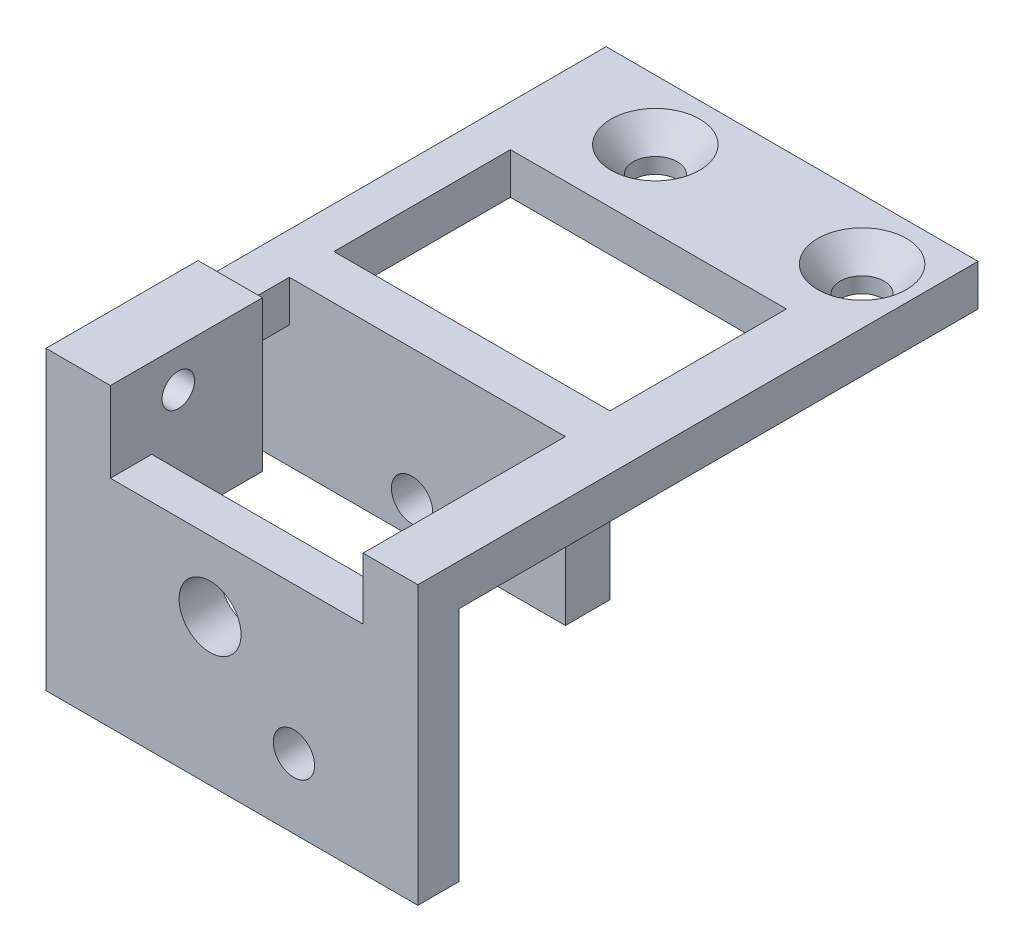
SolidWorks part; units mm, degrees
material "ABS"
ref_plane "Front Plane" through (0, 0, 0) normal (0, 0, 1) x (1, 0, 0)
ref_plane "Top Plane" through (0, 0, 0) normal (0, 1, 0) x (1, 0, 0)
ref_plane "Right Plane" through (0, 0, 0) normal (1, 0, 0) x (0, 0, -1)
sketch "Sketch1" plane through (0, 0, 0) normal (0, 0, 1) x (1, 0, 0)
  line L0 (0, 8.8442) -> (12.8921, -2.9343) construction
  line L1 (23.5226, 29.0697) -> (31.9421, 29.0697)
  line L2 (-25.2079, 8.8442) -> (-25.2079, -13.6023)
  line L3 (-25.2079, -13.6023) -> (31.9421, -13.6023)
  line L4 (31.9421, 29.0697) -> (31.9421, -13.6023)
  line L6 (-25.2079, 8.8442) -> (-25.2079, 31.9582)
  line L7 (-25.2079, 31.9582) -> (-18.8579, 31.9582)
  line L11 (23.5226, 22.6565) -> (23.5226, 29.0697)
  line L12 (-18.8579, 31.9582) -> (-15.3109, 31.9582)
  line L14 (-15.3109, 31.9582) -> (-15.3109, 22.6565)
  line L15 (-15.3109, 22.6565) -> (-15.3109, 19.6203)
  line L16 (-15.3109, 19.6203) -> (23.5226, 19.6203)
  line L17 (23.5226, 19.6203) -> (23.5226, 22.6565)
  circle A0 centre (12.8921, -2.9343) radius 3.175
  circle A1 centre (0, 8.8442) radius 4.7625
  dimension "D5" = 9.525
  dimension "D9" = 6.35
  dimension "D1" = 23.114
  dimension "D2" = 57.15
  dimension "D3" = 42.672
  dimension "D4" = 6.35
  dimension "D6" = 19.05
  dimension "D7" = 10.668
  dimension "D8" = 17.4625
extrude "Boss-Extrude1" add sketch "Sketch1" against normal blind 6.35
sketch "Sketch2" plane through (0, 0, 0) normal (0, 0, 1) x (1, 0, 0)
  line L0 (-25.2079, 31.9582) -> (-25.2079, -13.6023) construction
  line L1 (-18.8579, 31.9582) -> (-25.2079, 31.9582)
  line L3 (-18.8579, 8.8442) -> (-25.2079, 8.8442)
  line L4 (-25.2079, 31.9582) -> (-25.2079, 8.8442)
  line L6 (-15.3109, 31.9582) -> (-25.2079, 31.9582)
  line L7 (-15.3109, 31.9582) -> (-15.3109, 8.8442)
  line L8 (-15.3109, 8.8442) -> (-25.2079, 8.8442)
  line L9 (-25.2079, 31.9582) -> (-25.2079, 8.8442)
  line M4 (-15.3109, 31.9582) -> (-25.2079, 31.9582)
  line M5 (-25.2079, 31.9582) -> (-25.2079, -13.6023)
  line M15 (-15.3109, 19.6203) -> (-15.3109, 31.9582)
  dimension "D1" = 23.114
extrude "Boss-Extrude2" add sketch "Sketch2" against normal blind 23.368 contours L8 L7 L3 M15 M4 M5
sketch "Sketch3" plane through (0, 29.0697, 0) normal (0, 1, 0) x (1, 0, 0)
  line L0 (-25.2079, 23.368) -> (-25.2079, 0) construction
  line L1 (-18.8579, 0) -> (-25.2079, 0)
  line L2 (-18.8579, 0) -> (-18.8579, 78.34)
  line L3 (-18.8579, 78.34) -> (-25.2079, 78.34)
  line L4 (-25.2079, 0) -> (-25.2079, 78.34)
  line L5 (31.9421, 0) -> (23.5601, 0)
  line L6 (31.9421, 0) -> (31.9421, 78.34)
  line L7 (31.9421, 78.34) -> (23.5601, 78.34)
  line L8 (23.5601, 0) -> (23.5601, 78.34)
  dimension "D2" = 8.382
  dimension "D3" = 78.34
  dimension "D4" = 78.34
extrude "Boss-Extrude3" add sketch "Sketch3" against normal blind 6.35
sketch "Sketch4" plane through (-25.2079, 0, 0) normal (-1, 0, 0) x (0, 0, 1)
  circle A0 centre (-10.4375, 26.1623) radius 2.5
  dimension "D1" = 5
extrude "Cut-Extrude1" cut sketch "Sketch4" against normal up to next
sketch "Sketch5" plane through (0, 29.0697, 0) normal (0, 1, 0) x (1, 0, 0)
  line L0 (31.9421, 78.34) -> (31.9421, 0) construction
  line L2 (-25.2079, 78.34) -> (-25.2079, 65.0226)
  line L3 (-25.2079, 65.0226) -> (31.9421, 65.0226)
  line L4 (31.9421, 78.34) -> (31.9421, 65.0226)
  line L5 (-25.2079, 78.34) -> (-25.2079, 23.368) construction
  line L9 (-25.2079, 78.34) -> (-25.2079, 86.0813)
  line L10 (-25.2079, 86.0813) -> (31.9421, 86.0813)
  line L11 (31.9421, 78.34) -> (31.9421, 86.0813)
extrude "Boss-Extrude4" add sketch "Sketch5" against normal blind 6.35
hole_wizard "CSK for 1/4 Flat Head Machine Screw1" positions "Sketch6" profile "Sketch7" countersink size "1/4" standard "ANSI Inch" end condition through all
sketch "Sketch6" plane through (0, 29.0697, 0) normal (0, 1, 0) x (1, 0, 0)
  point P0 (-8.3847, 76.819)
  point P2 (23.3942, 76.819)
sketch "Sketch7" plane through (-8.3847, 29.0697, -76.819) normal (1, 0, 0) x (0, 0, 1)
  line L0 (0, 0) -> (0, 42.672)
  line L1 (0, 42.672) -> (3.3782, 42.672)
  line L2 (3.3782, 42.672) -> (3.3782, 3.9592)
  line L3 (3.3782, 3.9592) -> (6.8199, 0)
  line L5 (6.8199, 0) -> (0, 0)
  line L6 (-3.3782, 3.9592) -> (-6.8199, 0) construction
  line L11 (0, -6.35) -> (0, 107.95) construction
  dimension "Thru Hole Dia." = 6.7564
  dimension "Thru Hole Depth" = 42.672
  dimension "Near C'Sink Dia." = 13.6398
  dimension "Near C'Sink Angle" = 82
sketch "Sketch8" plane through (0, 29.0697, 0) normal (0, 1, 0) x (1, 0, 0)
  line L0 (-25.2079, 86.0813) -> (-25.2079, 23.368) construction
  line L10 (-25.2079, 37.893) -> (23.5601, 37.893)
  line L11 (23.5601, 65.0226) -> (23.5601, 6.35) construction
  line L12 (23.5601, 37.893) -> (23.5601, 31.05)
  line L13 (23.5601, 31.05) -> (-25.2079, 31.05)
  line L14 (-25.2079, 37.893) -> (-25.2079, 31.05)
extrude "Boss-Extrude5" add sketch "Sketch8" against normal blind 25.146
sketch "Sketch10" plane through (0, 0, -37.893) normal (0, 0, -1) x (-1, 0, 0)
  circle A0 centre (0, 8.8442) radius 3.175
  dimension "D1" = 6.35
extrude "Cut-Extrude2" cut sketch "Sketch10" against normal up to next
